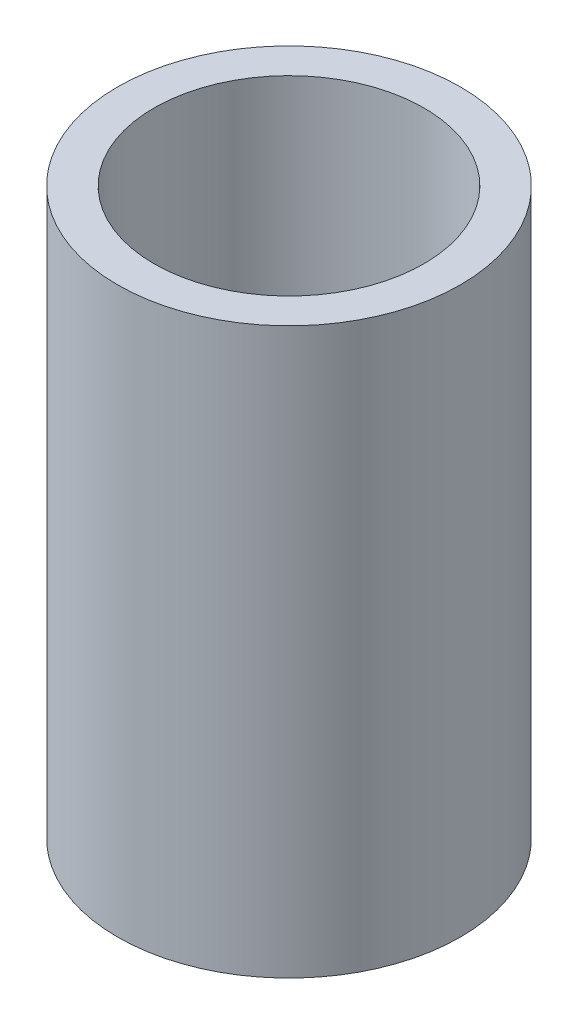
SolidWorks part; units mm, degrees
material "Custom Plastic"
ref_plane "X-Y Datum" through (0, 0, 0) normal (0, 0, 1) x (1, 0, 0)
ref_plane "X-Z Datum" through (0, 0, 0) normal (0, 1, 0) x (1, 0, 0)
ref_plane "Y-Z Datum" through (0, 0, 0) normal (1, 0, 0) x (0, 0, -1)
sketch "Sketch1" plane through (0, 0, 0) normal (0, 1, 0) x (1, 0, 0)
  circle A0 centre (0, 0) radius 2
  circle A1 centre (0, 0) radius 2.54
  dimension "D1" = 4
  dimension "D2" = 5.08
extrude "Boss-Extrude1" add sketch "Sketch1" against normal blind 8.37
